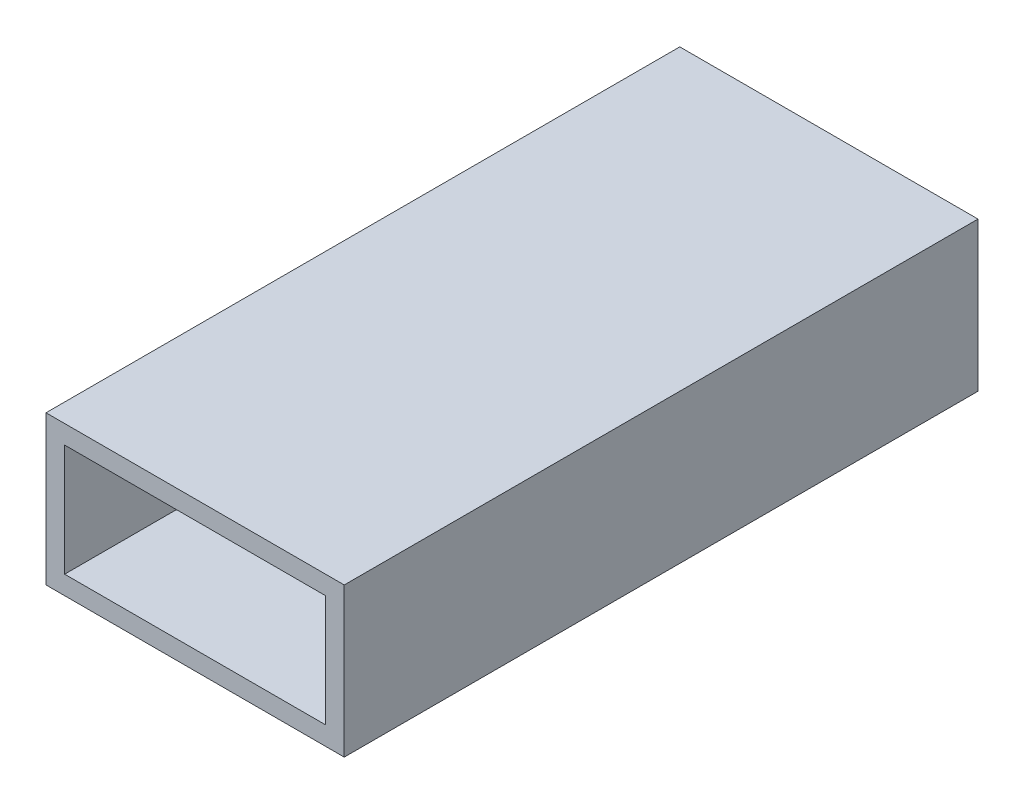
SolidWorks part; units mm, degrees
ref_plane "Front Plane" through (0, 0, 0) normal (0, 0, 1) x (1, 0, 0)
ref_plane "Top Plane" through (0, 0, 0) normal (0, 1, 0) x (1, 0, 0)
ref_plane "Right Plane" through (0, 0, 0) normal (1, 0, 0) x (0, 0, -1)
sketch "Sketch1" plane through (0, 0, 0) normal (0, 0, 1) x (1, 0, 0)
  line L1 (-990.7207, 634.9497) -> (-939.9207, 634.9497)
  line L2 (-990.7207, 634.9497) -> (-990.7207, 542.3575)
  line L3 (-990.7207, 542.3575) -> (-939.9207, 542.3575)
  line L4 (-939.9207, 634.9497) -> (-939.9207, 542.3575)
  line L10 (-990.7207, 542.3575) -> (-939.9207, 542.3575)
  line L11 (-990.7207, 542.3575) -> (-990.7207, 567.7575)
  line L12 (-990.7207, 567.7575) -> (-939.9207, 567.7575)
  line L13 (-939.9207, 542.3575) -> (-939.9207, 567.7575)
  circle A0 centre (-965.3752, 609.5497) radius 14.2875
  dimension "D2" = 25.4
  dimension "D1" = 50.8
extrude "Boss-Extrude1" add sketch "Sketch1" along normal blind 107.95 contours L12 L2 L3 L4
sketch "Sketch2" plane through (0, 0, 107.95) normal (0, 0, 1) x (1, 0, 0)
  line L0 (-990.7207, 567.7575) -> (-939.9207, 567.7575) construction
  line L1 (-987.5457, 564.5825) -> (-943.0957, 564.5825)
  line L2 (-987.5457, 564.5825) -> (-987.5457, 545.5325)
  line L3 (-987.5457, 545.5325) -> (-943.0957, 545.5325)
  line L4 (-943.0957, 564.5825) -> (-943.0957, 545.5325)
  line L5 (-990.7207, 567.7575) -> (-990.7207, 542.3575) construction
  line L6 (-990.7207, 542.3575) -> (-939.9207, 542.3575) construction
  line L7 (-939.9207, 567.7575) -> (-939.9207, 542.3575) construction
  dimension "D1" = 3.175
  dimension "D2" = 3.175
  dimension "D3" = 3.175
  dimension "D4" = 3.175
extrude "Cut-Extrude1" cut sketch "Sketch2" against normal through all
